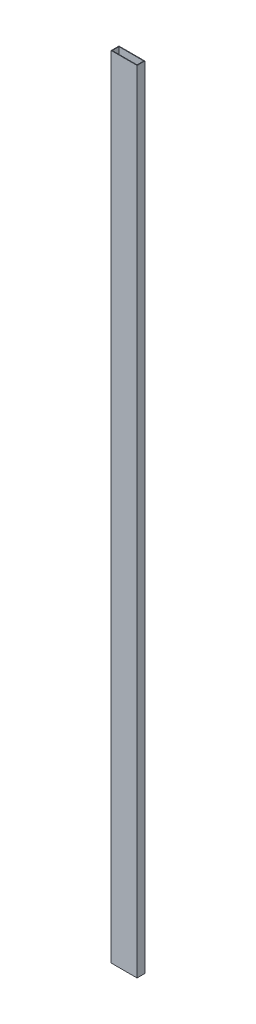
SolidWorks part; units mm, degrees
ref_plane "Front Plane" through (0, 0, 0) normal (0, 0, 1) x (1, 0, 0)
ref_plane "Top Plane" through (0, 0, 0) normal (0, 1, 0) x (1, 0, 0)
ref_plane "Right Plane" through (0, 0, 0) normal (1, 0, 0) x (0, 0, -1)
sketch "Sketch1" plane through (0, 0, 0) normal (0, 1, 0) x (1, 0, 0)
  line L0 (-48, -13) -> (-48, 13)
  line L1 (-50, -15) -> (50, -15)
  line L2 (-50, -15) -> (-50, 15)
  line L3 (-50, 15) -> (50, 15)
  line L4 (50, -15) -> (50, 15)
  line L5 (-50, -15) -> (50, 15) construction
  line L6 (-50, 15) -> (50, -15) construction
  line L7 (-48, 13) -> (48, 13)
  line L8 (48, -13) -> (48, 13)
  line L9 (-48, -13) -> (48, -13)
  point P0 (0, 0)
  dimension "D1" = 100
  dimension "D2" = 30
  dimension "D3" = 2
extrude "Boss-Extrude1" add sketch "Sketch1" along normal blind 3050
